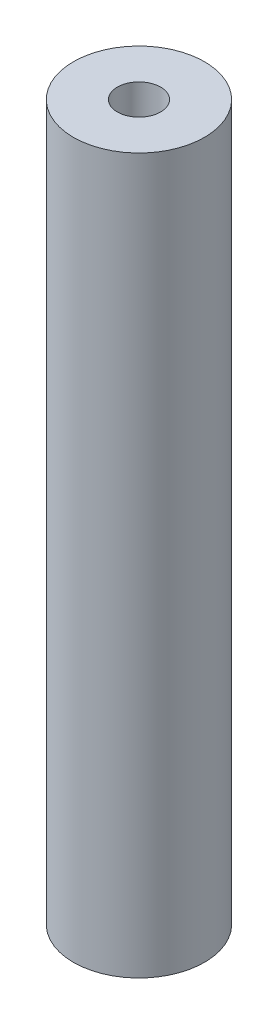
SolidWorks part; units mm, degrees
material "5052-H34"
ref_plane "正面" through (0, 0, 0) normal (0, 0, 1) x (1, 0, 0)
ref_plane "平面" through (0, 0, 0) normal (0, 1, 0) x (1, 0, 0)
ref_plane "右側面" through (0, 0, 0) normal (1, 0, 0) x (0, 0, -1)
sketch "ｽｹｯﾁ1" plane through (0, 0, 0) normal (0, 1, 0) x (1, 0, 0)
  circle A0 centre (0, 0) radius 5
  dimension "D1" = 10
extrude "ﾎﾞｽ - 押し出し1" add sketch "ｽｹｯﾁ1" along normal blind 54.5
hole_wizard "M4x0.7 ねじ穴1" positions "ｽｹｯﾁ2" profile "ｽｹｯﾁ3" tap size "M4x0.7" standard "JIS"
sketch "ｽｹｯﾁ2" plane through (0, 54.5, 0) normal (0, 1, 0) x (1, 0, 0)
  point P0 (0, 0)
sketch "ｽｹｯﾁ3" plane through (0, 54.5, 0) normal (1, 0, 0) x (0, 0, 1)
  line L0 (0, 0) -> (0, 15.9914)
  line L1 (0, 15.9914) -> (1.65, 15)
  line L2 (1.65, 15) -> (1.65, 0)
  line L5 (1.65, 0) -> (0, 0)
  line L10 (0, 15.9914) -> (-1.65, 15) construction
  line L11 (0, -6.35) -> (0, 107.95) construction
  dimension "ねじ下穴ﾄﾞﾘﾙ直径" = 3.3
  dimension "ねじ下穴ﾄﾞﾘﾙの深さ" = 15
  dimension "ﾄﾞﾘﾙ角度" = 118
ref_plane "平面1" through (0, 27.25, 0) normal (0, 1, 0) x (1, 0, 0)
mirror "ﾐﾗｰ1" about plane through (0, 27.25, 0) normal (0, 1, 0) of "M4x0.7 ねじ穴1"
